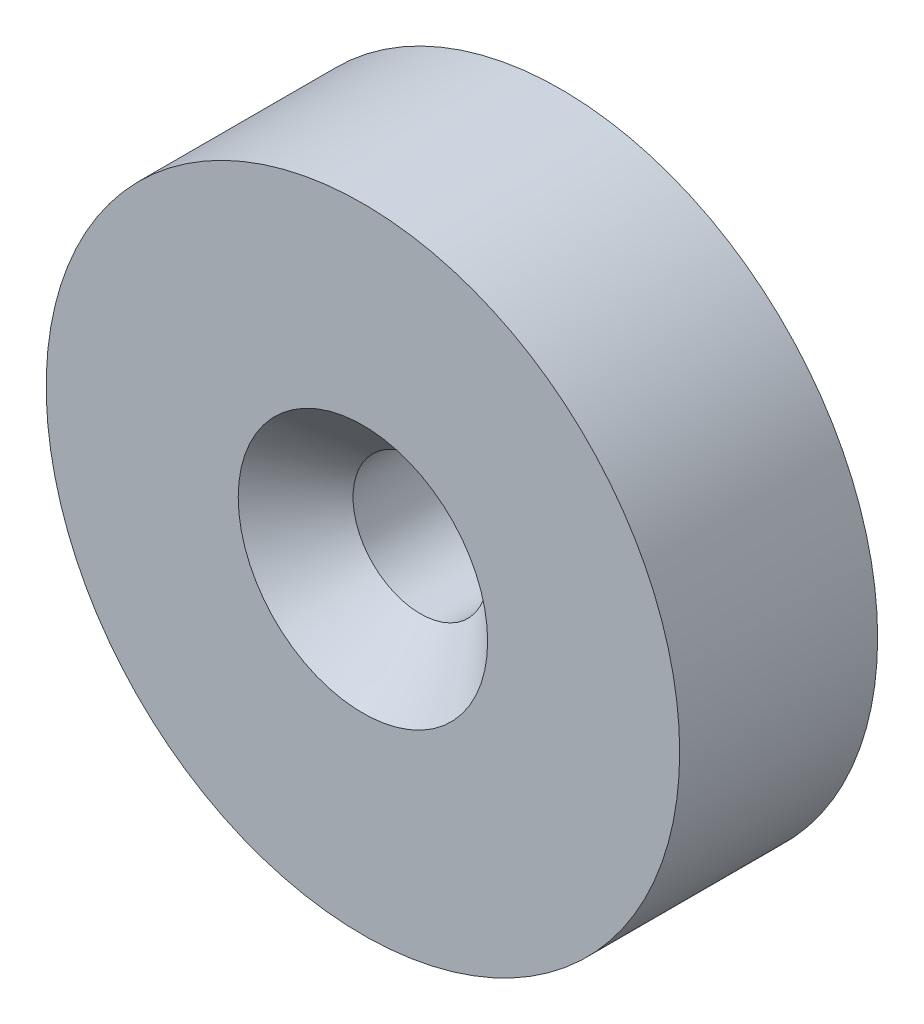
SolidWorks part; units mm, degrees
ref_plane "正面" through (0, 0, 0) normal (0, 0, 1) x (1, 0, 0)
ref_plane "平面" through (0, 0, 0) normal (0, 1, 0) x (1, 0, 0)
ref_plane "右側面" through (0, 0, 0) normal (1, 0, 0) x (0, 0, -1)
sketch "ｽｹｯﾁ1" plane through (0, 0, 0) normal (0, 0, 1) x (1, 0, 0)
  circle A0 centre (0, 0) radius 8
extrude "ﾎﾞｽ - 押し出し1" add sketch "ｽｹｯﾁ1" along normal blind 5
hole_wizard "M3 丸皿ねじ用皿穴2" positions "ｽｹｯﾁ2" profile "ｽｹｯﾁ3" countersink size "M3" standard "JIS" end condition through all
sketch "ｽｹｯﾁ2" plane through (0, 0, 5) normal (0, 0, 1) x (1, 0, 0)
  point P0 (0, 0)
sketch "ｽｹｯﾁ3" plane through (0, 0, 5) normal (1, 0, 0) x (0, -1, 0)
  line L0 (0, 0) -> (0, 5)
  line L1 (0, 5) -> (1.7, 5)
  line L2 (1.7, 5) -> (1.7, 1.45)
  line L3 (1.7, 1.45) -> (3.15, 0)
  line L5 (3.15, 0) -> (0, 0)
  line L6 (-1.7, 1.45) -> (-3.15, 0) construction
  line L11 (0, -6.35) -> (0, 107.95) construction
  dimension "通し穴の直径" = 3.4
  dimension "通し穴の深さ" = 5
  dimension "表面の皿穴の直径" = 6.3
  dimension "表面の皿穴の角度" = 90
